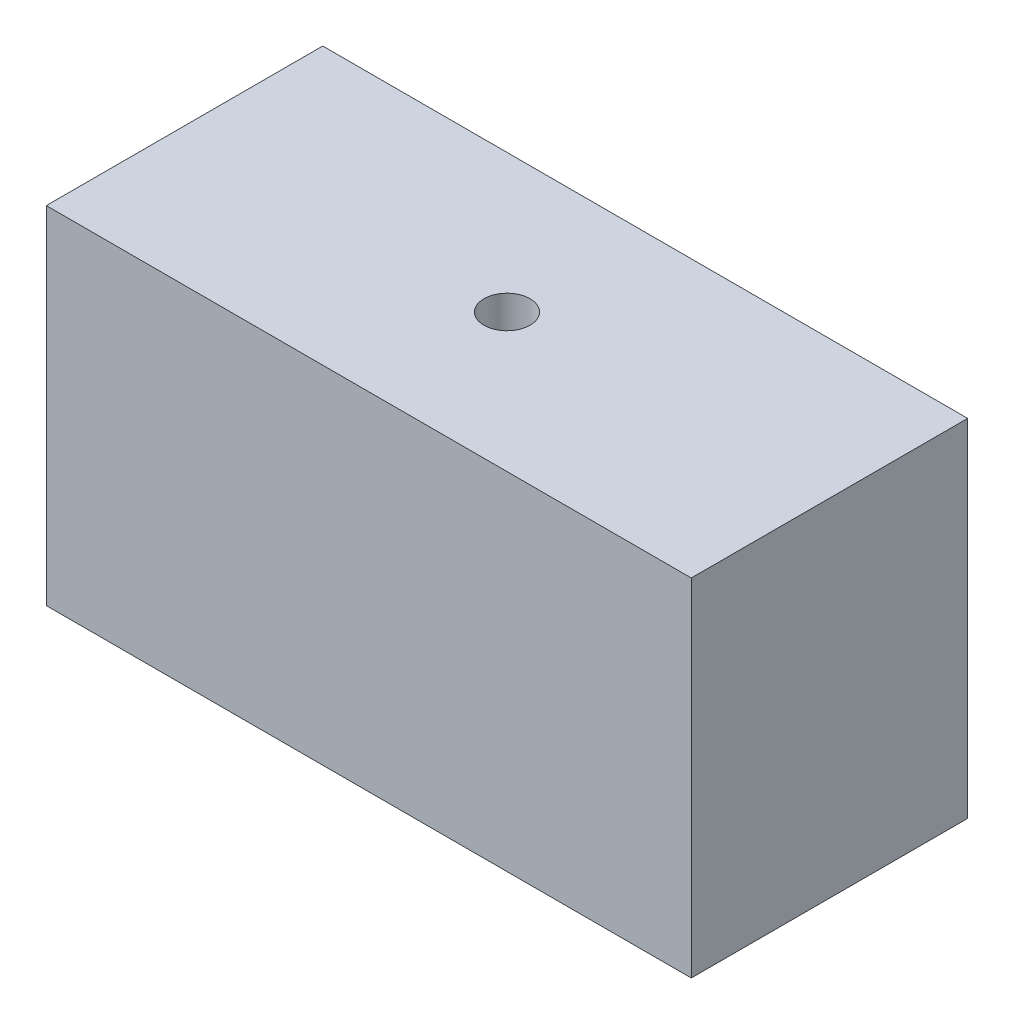
SolidWorks part; units mm, degrees
material "Balsa"
ref_plane "Front Plane" through (0, 0, 0) normal (0, 0, 1) x (1, 0, 0)
ref_plane "Top Plane" through (0, 0, 0) normal (0, 1, 0) x (1, 0, 0)
ref_plane "Right Plane" through (0, 0, 0) normal (1, 0, 0) x (0, 0, -1)
sketch "Sketch1" plane through (0, 0, 0) normal (0, 1, 0) x (1, 0, 0)
  line L1 (0, 0) -> (88.9, 0)
  line L2 (0, 0) -> (0, 38.1)
  line L3 (0, 38.1) -> (88.9, 38.1)
  line L4 (88.9, 0) -> (88.9, 38.1)
  circle A0 centre (44.45, 19.05) radius 3.175
  dimension "D3" = 6.35
  dimension "D4" = 19.05
  dimension "D5" = 44.45
  dimension "D1" = 38.1
  dimension "D2" = 88.9
extrude "Boss-Extrude1" add sketch "Sketch1" along normal blind 47.752
